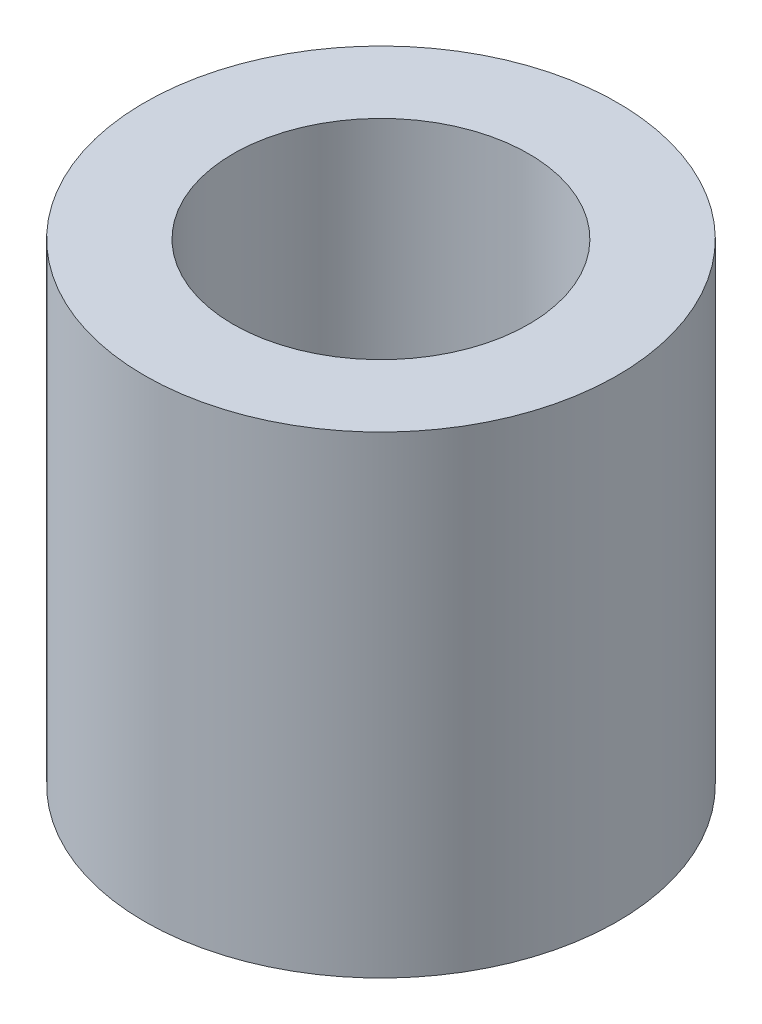
SolidWorks part; units mm, degrees
material "Brass"
ref_plane "Front Plane" through (0, 0, 0) normal (0, 0, 1) x (1, 0, 0)
ref_plane "Top Plane" through (0, 0, 0) normal (0, 1, 0) x (1, 0, 0)
ref_plane "Right Plane" through (0, 0, 0) normal (1, 0, 0) x (0, 0, -1)
sketch "Sketch1" plane through (0, 0, 0) normal (0, 1, 0) x (1, 0, 0)
  circle A0 centre (0, 0) radius 2.5
  circle A1 centre (0, 0) radius 4
  dimension "D1" = 5
  dimension "D2" = 8
extrude "Boss-Extrude1" add sketch "Sketch1" along normal blind 8 contours A1
